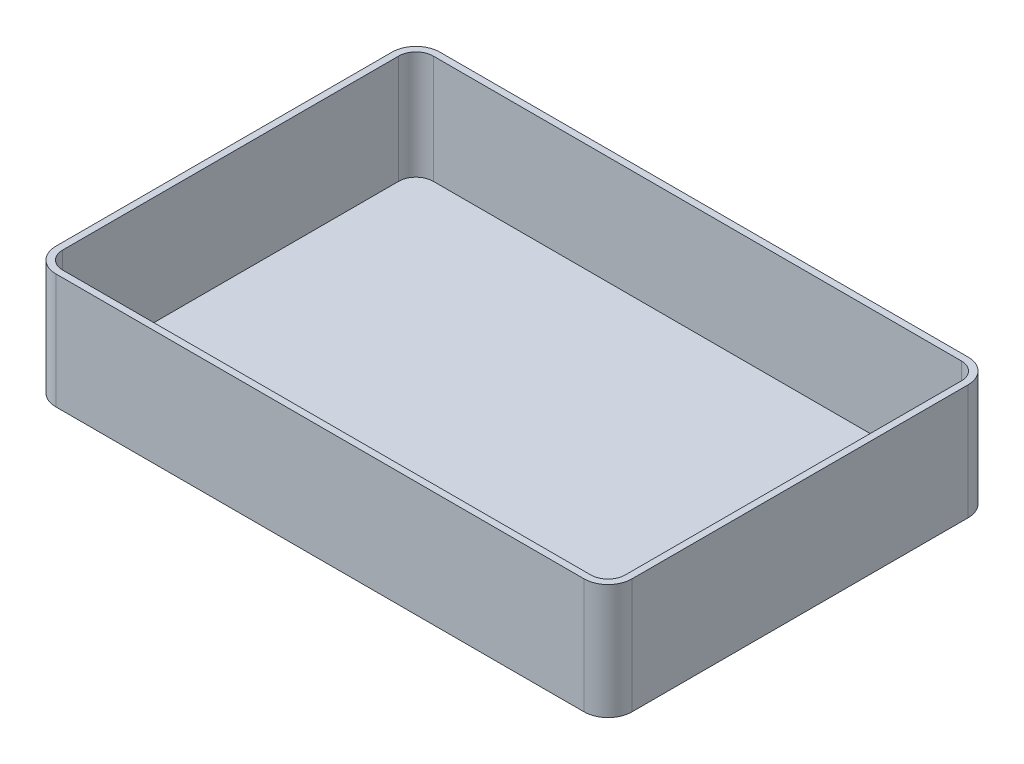
SolidWorks part; units mm, degrees
ref_plane "Front Plane" through (0, 0, 0) normal (0, 0, 1) x (1, 0, 0)
ref_plane "Top Plane" through (0, 0, 0) normal (0, 1, 0) x (1, 0, 0)
ref_plane "Right Plane" through (0, 0, 0) normal (1, 0, 0) x (0, 0, -1)
sketch "Sketch1" plane through (0, 0, 0) normal (0, 1, 0) x (1, 0, 0)
  line L1 (-275, -200) -> (275, -200)
  line L2 (-300, -175) -> (-300, 175)
  line L3 (-275, 200) -> (275, 200)
  line L4 (300, -175) -> (300, 175)
  line L5 (-300, -200) -> (300, 200) construction
  line L6 (-300, 200) -> (300, -200) construction
  arc A0 (275, 200) -> (300, 175) centre (275, 175) cw
  arc A1 (275, -200) -> (300, -175) centre (275, -175) ccw
  arc A2 (-275, -200) -> (-300, -175) centre (-275, -175) cw
  arc A3 (-300, 175) -> (-275, 200) centre (-275, 175) cw
  point P0 (0, 0)
  dimension "D3" = 25
  dimension "D1" = 600
  dimension "D2" = 400
extrude "Boss-Extrude1" add sketch "Sketch1" along normal blind 120
shell "Shell1" thickness 7
